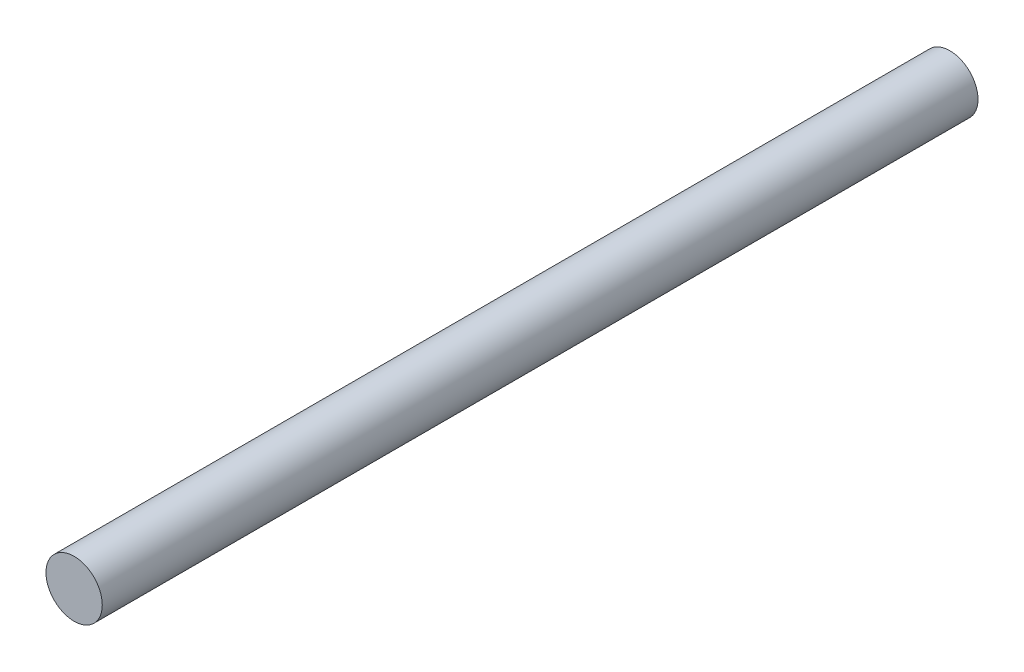
SolidWorks part; units mm, degrees
ref_plane "Front Plane" through (0, 0, 0) normal (0, 0, 1) x (1, 0, 0)
ref_plane "Top Plane" through (0, 0, 0) normal (0, 1, 0) x (1, 0, 0)
ref_plane "Right Plane" through (0, 0, 0) normal (1, 0, 0) x (0, 0, -1)
sketch "Sketch1" plane through (0, 0, 0) normal (0, 0, 1) x (1, 0, 0)
  circle A0 centre (0, 0) radius 8.89
  dimension "D1" = 17.78
extrude "Boss-Extrude1" add sketch "Sketch1" along normal blind 33.2 and the other way blind 243.2
